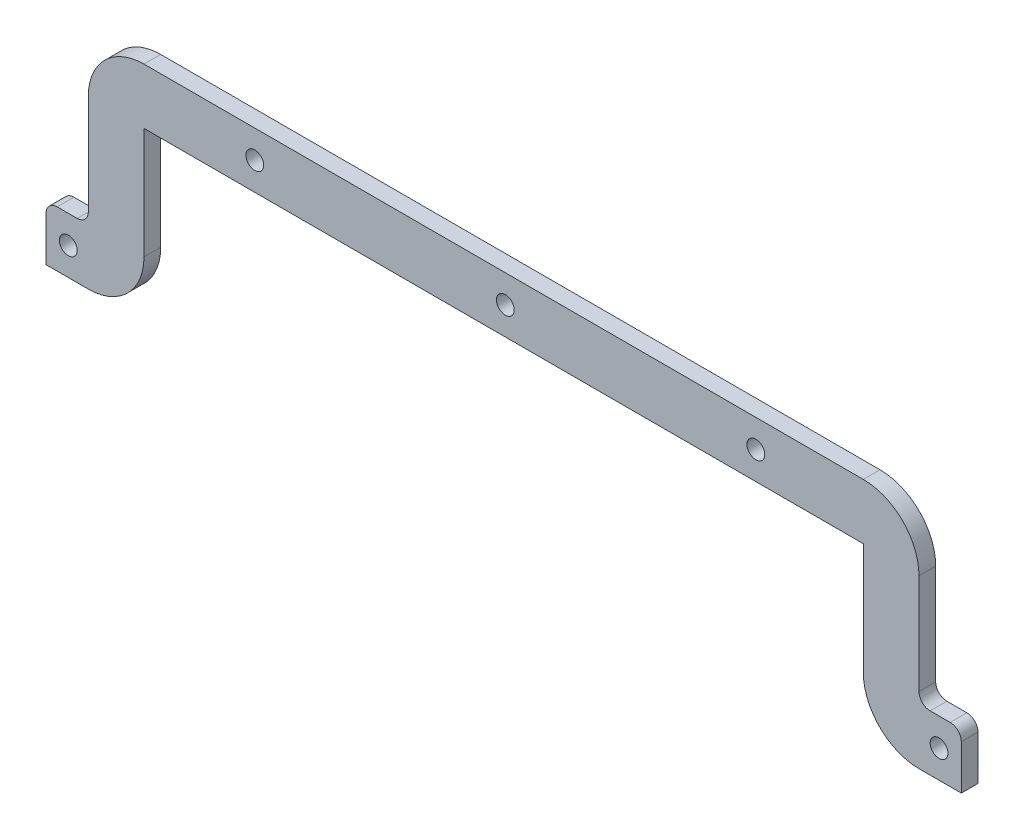
SolidWorks part; units mm, degrees
material "PUR"
ref_plane "Front Plane" through (0, 0, 0) normal (0, 0, 1) x (1, 0, 0)
ref_plane "Top Plane" through (0, 0, 0) normal (0, 1, 0) x (1, 0, 0)
ref_plane "Right Plane" through (0, 0, 0) normal (1, 0, 0) x (0, 0, -1)
sketch "Sketch2" plane through (0, 0, 0) normal (0, 0, 1) x (1, 0, 0)
  line L0 (7.7754, 8.7481) -> (7.7754, -4.7183) construction
  line L1 (-74.4246, -1.2519) -> (-56.8246, -1.2519)
  line L2 (-74.4246, -1.2519) -> (-74.4246, 8.7481)
  line L3 (-74.4246, 8.7481) -> (-66.8246, 8.7481)
  line L4 (89.9754, -1.2519) -> (89.9754, 8.7481)
  line L5 (-66.8246, 8.7481) -> (-66.8246, 38.7481)
  line L6 (-66.8246, 38.7481) -> (82.3754, 38.7481)
  line L7 (82.3754, 38.7481) -> (82.3754, 8.7481)
  line L8 (-56.8246, -1.2519) -> (-56.8246, 28.7481)
  line L9 (72.3754, -1.2519) -> (89.9754, -1.2519)
  line L10 (72.3754, 28.7481) -> (72.3754, -1.2519)
  line L11 (-56.8246, 28.7481) -> (72.3754, 28.7481)
  line L13 (82.3754, 8.7481) -> (89.9754, 8.7481)
  circle A0 centre (-70.4246, 3.7481) radius 1.6
  circle A1 centre (85.9754, 3.7481) radius 1.6
  dimension "D3" = 3.2
  dimension "D11" = 4
  dimension "D1" = 164.4
  dimension "D2" = 10
  dimension "D4" = 4
  dimension "D5" = 5
  dimension "D6" = 7.6
  dimension "D7" = 7.6
  dimension "D8" = 10
  dimension "D9" = 10
  dimension "D10" = 30
  dimension "D12" = 30
extrude "Boss-Extrude1" add sketch "Sketch2" along normal blind 3
sketch "Sketch3" plane through (0, 0, 3) normal (0, 0, 1) x (1, 0, 0)
  line L0 (-74.4246, 33.7481) -> (-59.2246, 33.7481) construction
  line L3 (82.3754, 38.7481) -> (-66.8246, 38.7481) construction
  circle A0 centre (-70.4246, 3.7481) radius 1.6 construction
  circle A2 centre (-36.9246, 33.7481) radius 1.6
  circle A4 centre (8.0754, 33.7481) radius 1.6
  circle A5 centre (53.0754, 33.7481) radius 1.6
  dimension "D1" = 3.2
  dimension "D2" = 33.5
  dimension "D4" = 5
  dimension "D5" = 5
  dimension "D3" = 3
extrude "Cut-Extrude1" cut sketch "Sketch3" against normal up to next
fillet "Fillet1" radius 10 4 edges at (72.3754, -1.2519, 1.5) (-56.8246, -1.2519, 1.5) (82.3754, 38.7481, 1.5) (-66.8246, 38.7481, 1.5)
fillet "Fillet2" radius 2 4 edges at (82.3754, 8.7481, 1.5) (-66.8246, 8.7481, 1.5) (89.9754, 8.7481, 1.5) (-74.4246, 8.7481, 1.5)
